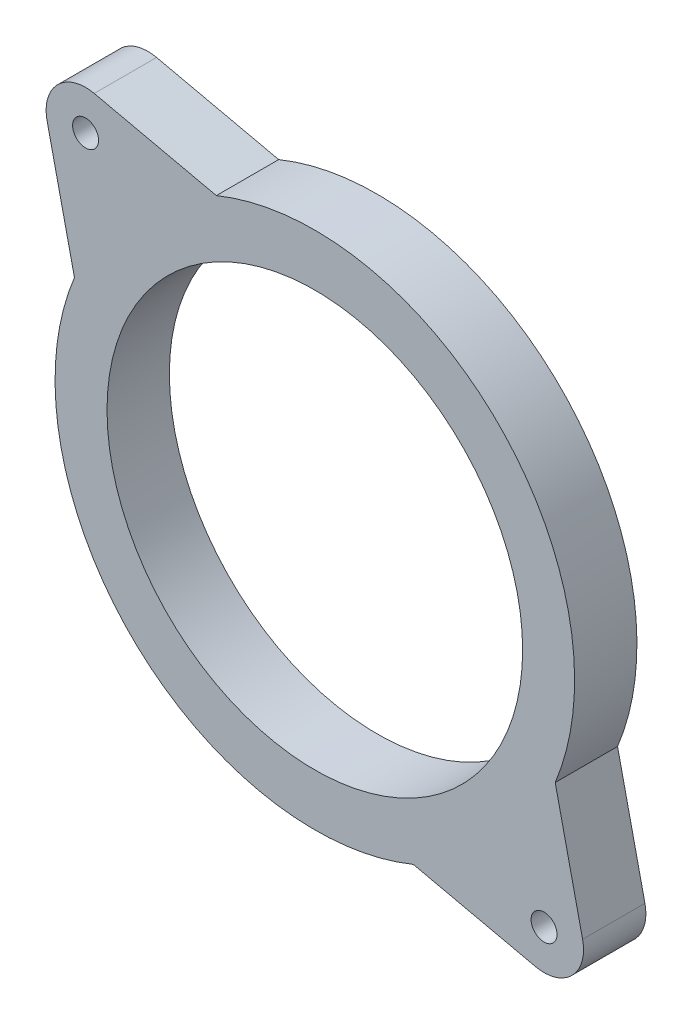
SolidWorks part; units mm, degrees
ref_plane "Спереди" through (0, 0, 0) normal (0, 0, 1) x (1, 0, 0)
ref_plane "Сверху" through (0, 0, 0) normal (0, 1, 0) x (1, 0, 0)
ref_plane "Справа" through (0, 0, 0) normal (1, 0, 0) x (0, 0, -1)
sketch "Эскиз1" plane through (0, 0, 0) normal (0, 0, 1) x (1, 0, 0)
  line L0 (9.4769, -23.1341) -> (21.2303, -25.7697)
  line L1 (25.7697, -21.2303) -> (23.1341, -9.4769)
  line L2 (-9.4769, 23.1341) -> (-21.2303, 25.7697)
  line L3 (-25.7697, 21.2303) -> (-23.1341, 9.4769)
  arc A1 (21.2303, -25.7697) -> (25.7697, -21.2303) centre (22.0617, -22.0617) ccw
  arc A3 (-21.2303, 25.7697) -> (-25.7697, 21.2303) centre (-22.0617, 22.0617) ccw
  arc A4 (-23.1341, 9.4769) -> (9.4769, -23.1341) centre (0, 0) ccw
  arc A5 (23.1341, -9.4769) -> (-9.4769, 23.1341) centre (0, 0) ccw
  circle A6 centre (0, 0) radius 20
extrude "Бобышка-Вытянуть1" add sketch "Эскиз1" along normal blind 6
hole_wizard "Отверстие обработанное метчиком M31" positions "Эскиз2" profile "Эскиз3" tap size "M3" standard "ISO" end condition through all
sketch "Эскиз2" plane through (0, 0, 6) normal (0, 0, 1) x (1, 0, 0)
  point P0 (-22.0617, 22.0617)
  point P3 (22.0617, -22.0617)
sketch "Эскиз3" plane through (-22.0617, 22.0617, 6) normal (1, 0, 0) x (0, -1, 0)
  line L0 (0, 0) -> (0, 6)
  line L1 (0, 6) -> (1.25, 6)
  line L2 (1.25, 6) -> (1.25, 0)
  line L5 (1.25, 0) -> (0, 0)
  line L11 (0, -6.35) -> (0, 107.95) construction
  dimension "Диаметр проходного сверла" = 2.5
  dimension "Глубина проходного сверла" = 6
cosmetic thread "Отверстие резьбы1" parameters "D2"=3
cosmetic thread "Отверстие резьбы2" parameters "D2"=3
